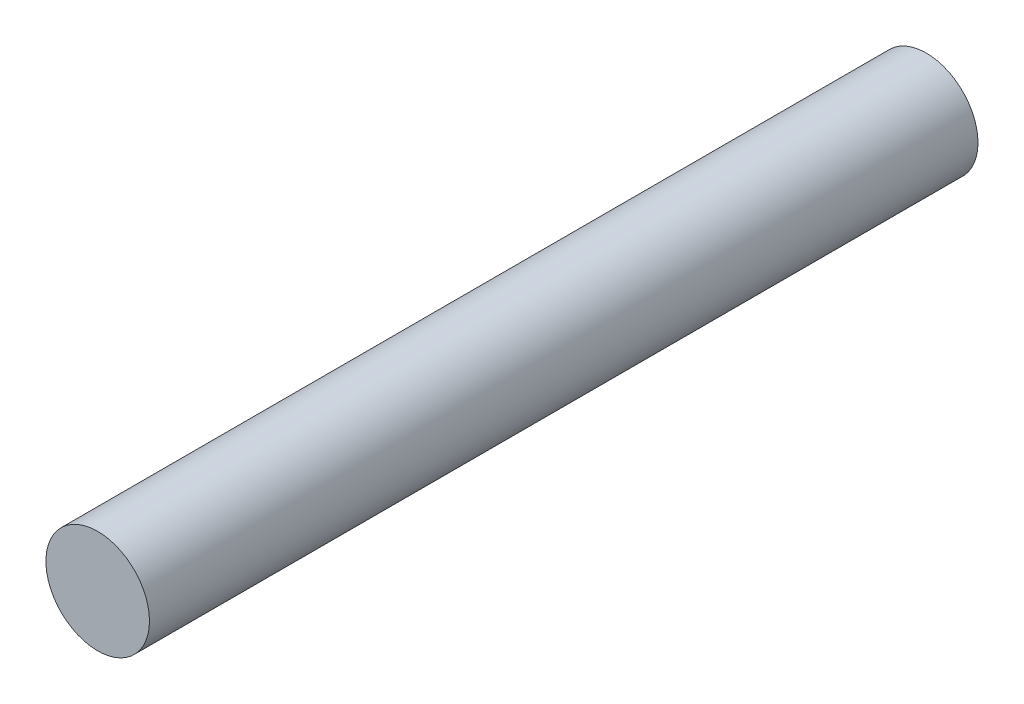
SolidWorks part; units mm, degrees
ref_plane "Front Plane" through (0, 0, 0) normal (0, 0, 1) x (1, 0, 0)
ref_plane "Top Plane" through (0, 0, 0) normal (0, 1, 0) x (1, 0, 0)
ref_plane "Right Plane" through (0, 0, 0) normal (1, 0, 0) x (0, 0, -1)
sketch "Sketch1" plane through (0, 0, 0) normal (0, 0, 1) x (1, 0, 0)
  circle A0 centre (0, 0) radius 25
  dimension "D1" = 50
extrude "Boss-Extrude1" add sketch "Sketch1" along normal blind 400
